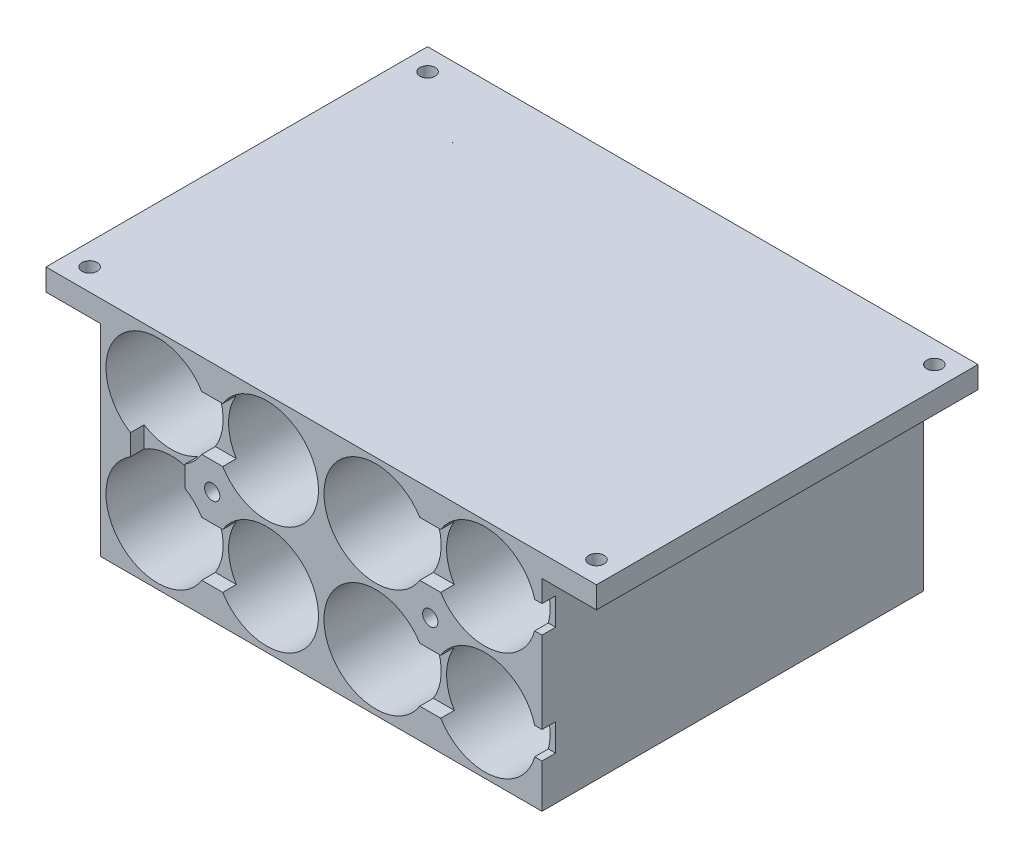
SolidWorks part; units mm, degrees
ref_plane "Front" through (0, 0, 0) normal (0, 0, 1) x (1, 0, 0)
ref_plane "Top" through (0, 0, 0) normal (0, 1, 0) x (1, 0, 0)
ref_plane "Right" through (0, 0, 0) normal (1, 0, 0) x (0, 0, -1)
sketch "Sketch1" plane through (0, 0, 0) normal (0, 0, 1) x (1, 0, 0)
  line L1 (0, 0) -> (81, 0)
  line L2 (0, 0) -> (0, 41)
  line L3 (0, 41) -> (81, 41)
  line L4 (81, 0) -> (81, 41)
  dimension "D1" = 41
  dimension "D2" = 81
extrude "Boss-Extrude1" add sketch "Sketch1" along normal blind 70
sketch "Sketch2" plane through (0, 0, 70) normal (0, 0, 1) x (1, 0, 0)
  line L0 (0, 41) -> (0, 0) construction
  line L1 (81, 41) -> (0, 41) construction
  circle A0 centre (10.5, 30.5) radius 9.5
  circle A1 centre (30.5, 30.5) radius 9.5
  circle A2 centre (50.5, 30.5) radius 9.5
  circle A3 centre (70.5, 30.5) radius 9.5
  circle A4 centre (30.5, 10.5) radius 9.5
  circle A5 centre (50.5, 10.5) radius 9.5
  circle A6 centre (70.5, 10.5) radius 9.5
  circle A7 centre (10.5, 10.5) radius 9.5
  dimension "D1" = 19
  dimension "D2" = 10.5
  dimension "D3" = 10.5
  dimension "D4" = 4
  dimension "D5" = 2
extrude "Cut-Extrude1" cut sketch "Sketch2" against normal through all
sketch "Sketch3" plane through (0, 0, 0) normal (-1, 0, 0) x (0, 0, 1)
  line L0 (0, 41) -> (0, 0) construction
  line L1 (70, 41) -> (0, 41)
  line L2 (70, 41) -> (70, 37)
  line L3 (70, 37) -> (0, 37)
  line L4 (0, 41) -> (0, 37)
  dimension "D1" = 4
extrude "Boss-Extrude2" add sketch "Sketch3" along normal blind 10
sketch "Sketch4" plane through (81, 0, 0) normal (1, 0, 0) x (0, 0, -1)
  line L0 (0, 0) -> (0, 41) construction
  line L1 (-70, 41) -> (0, 41)
  line L2 (-70, 41) -> (-70, 37)
  line L3 (-70, 37) -> (0, 37)
  line L4 (0, 41) -> (0, 37)
  dimension "D1" = 4
extrude "Boss-Extrude3" add sketch "Sketch4" along normal blind 10
sketch "Sketch5" plane through (0, 41, 0) normal (0, 1, 0) x (1, 0, 0)
  line L0 (91, 0) -> (-10, 0) construction
  line L1 (-10, -70) -> (-10, 0) construction
  line L2 (91, -70) -> (-10, -70) construction
  line L3 (91, 0) -> (91, -70) construction
  circle A0 centre (-6, -4) radius 1.4
  circle A1 centre (-6, -66) radius 1.4
  circle A2 centre (87, -66) radius 1.4
  circle A3 centre (87, -4) radius 1.4
  dimension "D3" = 2.8
  dimension "D8" = 2.8
  dimension "D9" = 2.8
  dimension "D12" = 2.8
  dimension "D1" = 4
  dimension "D2" = 4
  dimension "D4" = 4
  dimension "D5" = 4
  dimension "D6" = 4
  dimension "D7" = 4
  dimension "D10" = 4
  dimension "D11" = 4
extrude "Cut-Extrude2" cut sketch "Sketch5" against normal through all
sketch "Sketch6" plane through (0, 0, 70) normal (0, 0, 1) x (1, 0, 0)
  line L0 (0, 0) -> (81, 0) construction
  line L1 (15.4245, 35.5) -> (25.4245, 35.5)
  line L2 (15.4245, 35.5) -> (15.4245, 25.5)
  line L3 (15.4245, 25.5) -> (25.4245, 25.5)
  line L4 (25.4245, 35.5) -> (25.4245, 25.5)
  line L5 (54.8586, 35.5) -> (64.8586, 35.5)
  line L6 (54.8586, 35.5) -> (54.8586, 25.5)
  line L7 (54.8586, 25.5) -> (64.8586, 25.5)
  line L8 (64.8586, 35.5) -> (64.8586, 25.5)
  line L9 (15.4245, 15.5) -> (25.4245, 15.5)
  line L10 (15.4245, 15.5) -> (15.4245, 5.5)
  line L11 (15.4245, 5.5) -> (25.4245, 5.5)
  line L12 (25.4245, 15.5) -> (25.4245, 5.5)
  line L13 (54.8586, 15.5) -> (64.8586, 15.5)
  line L14 (54.8586, 15.5) -> (54.8586, 5.5)
  line L15 (54.8586, 5.5) -> (64.8586, 5.5)
  line L16 (64.8586, 15.5) -> (64.8586, 5.5)
  line L17 (91, 41) -> (-10, 41) construction
  dimension "D10" = 5.5
  dimension "D1" = 10
  dimension "D2" = 10
  dimension "D3" = 10
  dimension "D4" = 10
  dimension "D5" = 10
  dimension "D6" = 10
  dimension "D7" = 10
  dimension "D8" = 10
  dimension "D9" = 5.5
  dimension "D11" = 5.5
  dimension "D12" = 5.5
extrude "Cut-Extrude3" cut sketch "Sketch6" against normal blind 2.5
sketch "Sketch7" plane through (0, 0, 0) normal (0, 0, -1) x (-1, 0, 0)
  line L0 (0, 0) -> (-81, 0) construction
  line L1 (-66, 35.5) -> (-56, 35.5)
  line L2 (-66, 35.5) -> (-66, 25.5)
  line L3 (-66, 25.5) -> (-56, 25.5)
  line L4 (-56, 35.5) -> (-56, 25.5)
  line L5 (-25, 35.5) -> (-15, 35.5)
  line L6 (-25, 35.5) -> (-25, 25.5)
  line L7 (-25, 25.5) -> (-15, 25.5)
  line L8 (-15, 35.5) -> (-15, 25.5)
  line L9 (-25, 15.5) -> (-15, 15.5)
  line L10 (-25, 15.5) -> (-25, 5.5)
  line L11 (-25, 5.5) -> (-15, 5.5)
  line L12 (-15, 15.5) -> (-15, 5.5)
  line L13 (-56, 5.5) -> (-66, 5.5)
  line L14 (-56, 5.5) -> (-56, 15.5)
  line L15 (-56, 15.5) -> (-66, 15.5)
  line L16 (-66, 5.5) -> (-66, 15.5)
  line L17 (-91, 41) -> (10, 41) construction
  line L18 (-81, 0) -> (-81, 37) construction
  line L19 (0, 37) -> (0, 0) construction
  dimension "D1" = 10
  dimension "D2" = 10
  dimension "D3" = 10
  dimension "D4" = 10
  dimension "D5" = 10
  dimension "D6" = 10
  dimension "D7" = 10
  dimension "D8" = 10
  dimension "D9" = 5.5
  dimension "D10" = 5.5
  dimension "D11" = 5.5
  dimension "D12" = 5.5
  dimension "D13" = 15
  dimension "D14" = 15
  dimension "D15" = 15
  dimension "D16" = 15
extrude "Cut-Extrude4" cut sketch "Sketch7" against normal blind 2.5
sketch "Sketch8" plane through (0, 0, 0) normal (0, 0, -1) x (-1, 0, 0)
  line L0 (0, 37) -> (0, 0) construction
  line L1 (-45, 35.5) -> (-35, 35.5)
  line L2 (-45, 35.5) -> (-45, 25.5)
  line L3 (-45, 25.5) -> (-35, 25.5)
  line L4 (-35, 35.5) -> (-35, 25.5)
  line L5 (-45, 15.5) -> (-35, 15.5)
  line L6 (-45, 15.5) -> (-45, 5.5)
  line L7 (-45, 5.5) -> (-35, 5.5)
  line L8 (-35, 15.5) -> (-35, 5.5)
  line L9 (0, 0) -> (-81, 0) construction
  line L10 (-91, 41) -> (10, 41) construction
  dimension "D1" = 10
  dimension "D2" = 10
  dimension "D3" = 10
  dimension "D4" = 10
  dimension "D5" = 35
  dimension "D6" = 35
  dimension "D7" = 5.5
  dimension "D8" = 5.5
extrude "Cut-Extrude5" cut sketch "Sketch8" against normal blind 2.5
sketch "Sketch9" plane through (0, 0, 70) normal (0, 0, 1) x (1, 0, 0)
  line L0 (0, 0) -> (81, 0) construction
  line L1 (5.5, 25.5) -> (15.5, 25.5)
  line L2 (5.5, 25.5) -> (5.5, 15.5)
  line L3 (5.5, 15.5) -> (15.5, 15.5)
  line L4 (15.5, 25.5) -> (15.5, 15.5)
  line L5 (74, 33) -> (84, 33)
  line L6 (74, 33) -> (74, 28)
  line L7 (74, 28) -> (84, 28)
  line L8 (84, 33) -> (84, 28)
  line L9 (74, 13) -> (84, 13)
  line L10 (74, 13) -> (74, 8)
  line L11 (74, 8) -> (84, 8)
  line L12 (84, 13) -> (84, 8)
  line L13 (91, 41) -> (-10, 41) construction
  line L14 (81, 0) -> (81, 37) construction
  line L15 (0, 37) -> (0, 0) construction
  dimension "D1" = 10
  dimension "D2" = 10
  dimension "D3" = 10
  dimension "D4" = 5
  dimension "D5" = 10
  dimension "D6" = 5
  dimension "D7" = 8
  dimension "D8" = 8
  dimension "D9" = 3
  dimension "D10" = 3
  dimension "D11" = 5.5
  dimension "D12" = 15.5
extrude "Cut-Extrude6" cut sketch "Sketch9" against normal blind 2.5
sketch "Sketch10" plane through (0, 0, 70) normal (0, 0, 1) x (1, 0, 0)
  line L0 (91, 41) -> (-10, 41) construction
  line L1 (81, 13) -> (81, 28) construction
  line L2 (0, 37) -> (0, 0) construction
  circle A0 centre (20.5, 20.5) radius 1.4
  circle A1 centre (60.5, 20.5) radius 1.4
  dimension "D5" = 2.8
  dimension "D6" = 2.8
  dimension "D1" = 20.5
  dimension "D2" = 20.5
  dimension "D3" = 20.5
  dimension "D4" = 20.5
extrude "Cut-Extrude7" cut sketch "Sketch10" against normal through all
